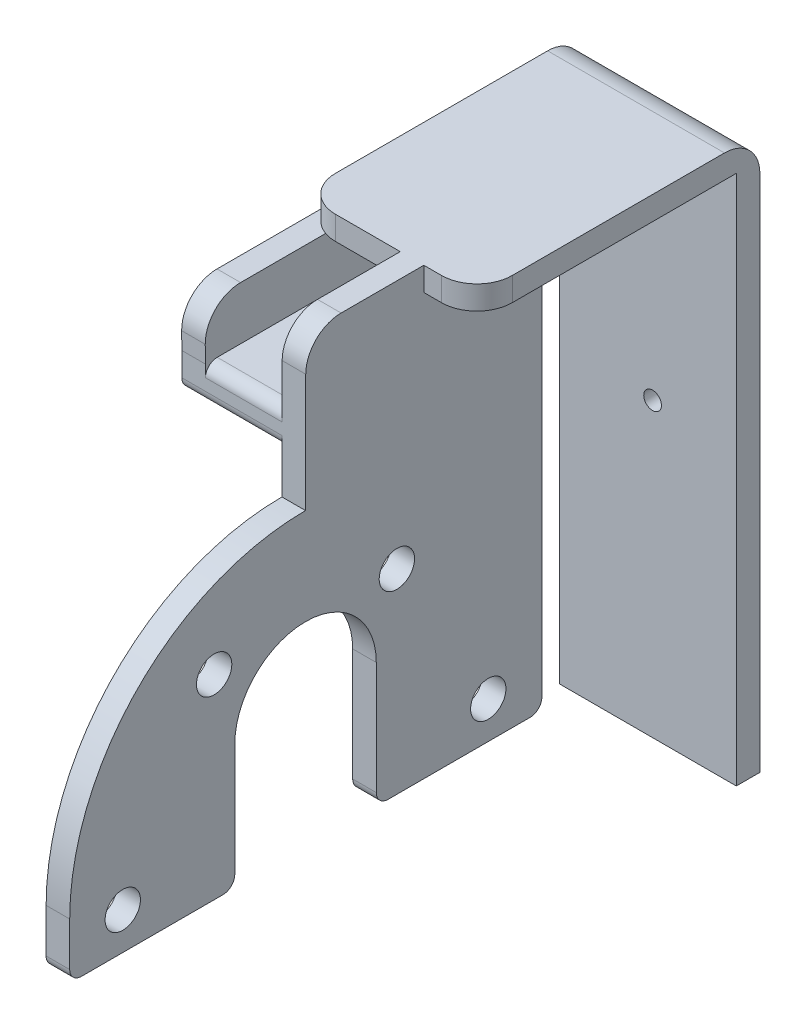
SolidWorks part; units mm, degrees
ref_plane "Front Plane" through (0, 0, 0) normal (0, 0, 1) x (1, 0, 0)
ref_plane "Top Plane" through (0, 0, 0) normal (0, 1, 0) x (1, 0, 0)
ref_plane "Right Plane" through (0, 0, 0) normal (1, 0, 0) x (0, 0, -1)
sketch "Sketch1" plane through (0, 0, 0) normal (0, 1, 0) x (1, 0, 0)
  line L0 (0, 21) -> (0, -134) construction
  line L2 (55, -27) -> (55, 27)
  line L3 (55, 27) -> (-55, 27)
  line L4 (-55, -27) -> (-55, 27)
  line L5 (55, -27) -> (-55, 27) construction
  line L6 (55, 27) -> (-55, -27) construction
  line L7 (-38.5, -134) -> (38.5, -134)
  line L8 (-55, -27) -> (-38.5, -134)
  line L9 (55, -27) -> (38.5, -134)
  line L10 (0, -134) -> (0, -281.2906)
  line L11 (64, -159) -> (-64, -159)
  line L12 (64, -159) -> (64, -134)
  line L13 (64, -134) -> (-64, -134)
  line L14 (-64, -159) -> (-64, -134)
  line L15 (64, -159) -> (-64, -134) construction
  line L16 (64, -134) -> (-64, -159) construction
  line L17 (31, -159) -> (-31, -159)
  line L18 (31, -159) -> (31, -172)
  line L19 (31, -172) -> (-31, -172)
  line L20 (-31, -159) -> (-31, -172)
  line L21 (31, -159) -> (-31, -172) construction
  line L22 (31, -172) -> (-31, -159) construction
  line L23 (64, -172) -> (-64, -172)
  line L24 (64, -172) -> (64, -203)
  line L25 (64, -203) -> (-64, -203)
  line L26 (-64, -172) -> (-64, -203)
  line L27 (64, -172) -> (-64, -203) construction
  line L28 (64, -203) -> (-64, -172) construction
  line L29 (0, 21) -> (0, 27)
  point P0 (0, 0)
  point P10 (0, -134)
  point P11 (0, -146.5)
  point P16 (0, -165.5)
  point P21 (0, -187.5)
  point P26 (0, -134)
  point P28 (0, -159)
  point P29 (0, 27)
  point P33 (0, -172)
  dimension "D1" = 110
  dimension "D2" = 54
  dimension "D3" = 155
  dimension "D4" = 77
  dimension "D5" = 25
  dimension "D6" = 31
  dimension "D7" = 13
  dimension "D8" = 128
  dimension "D9" = 128
  dimension "D10" = 62
  dimension "D11" = 230
  dimension "D12" = 107
extrude "Boss-Extrude1" add sketch "Sketch1" along normal blind 2
sketch "Sketch2" plane through (-55, 0, 0) normal (-1, 0, 0) x (0, 0, 1)
  line L0 (-27, 2) -> (-23, 2)
  line L1 (27, 2) -> (-27, 2) construction
  line L2 (-23, 2) -> (17, 2)
  line L3 (-23, 2) -> (-23, 42)
  line L4 (17, 2) -> (17, 42)
  line L5 (-23, 24) -> (17, 24) construction
  arc A0 (-23, 24) -> (17, 24) centre (-3, 24) cw
  point P5 (-23, 24)
  point P11 (-3, 24)
  line M8 (27, 2) -> (-27, 2)
  dimension "D1" = 4
  dimension "D2" = 40
  dimension "D3" = 40
  dimension "D4" = 40
  dimension "D5" = 22
extrude "Boss-Extrude2" add sketch "Sketch2" against normal blind 2 contours A0 L5 | L5 L3 L4 M8
sketch "Sketch3" plane through (-55, 0, 0) normal (-1, 0, 0) x (0, 0, 1)
  line L0 (-3, 0) -> (-3, 16)
  line L1 (27, 0) -> (-27, 0) construction
  line L2 (-23, 2) -> (-23, 24) construction
  circle A0 centre (-3, 16) radius 6
  dimension "D3" = 12
  dimension "D1" = 16
  dimension "D2" = 20
extrude "Cut-Extrude1" cut sketch "Sketch3" against normal blind 2
mirror "Mirror1" about plane through (0, 0, 0) normal (1, 0, 0) of "Boss-Extrude2"
mirror "Mirror2" about plane through (0, 0, 0) normal (1, 0, 0) of "Cut-Extrude1"
sketch "Sketch4" plane through (0, 2, 0) normal (0, 1, 0) x (1, 0, 0)
  line L0 (0, 27) -> (0, -33) construction
  line L1 (55, 27) -> (-55, 27) construction
  line L2 (0, -33) -> (0, -103) construction
  line L3 (32, -33) -> (-32, -33) construction
  line L4 (32, -103) -> (-32, -103) construction
  circle A0 centre (-32, -33) radius 1.5
  circle A1 centre (-32, -103) radius 1.5
  circle A2 centre (32, -103) radius 1.5
  circle A3 centre (32, -33) radius 1.5
  point P9 (0, -33)
  point P12 (0, -103)
  dimension "D5" = 3
  dimension "D6" = 3
  dimension "D7" = 3
  dimension "D8" = 3
  dimension "D1" = 60
  dimension "D2" = 70
  dimension "D3" = 64
  dimension "D4" = 64
extrude "Cut-Extrude2" cut sketch "Sketch4" against normal blind 3
sketch "Sketch5" plane through (0, 2, 0) normal (0, 1, 0) x (1, 0, 0)
  line L0 (0, -206.875) -> (0, 38.2082) construction
  line L1 (64, -203) -> (-64, -203) construction
  line L2 (0, -203) -> (0, -196)
  line L3 (42, -196) -> (-42, -196)
  circle A0 centre (0, -196) radius 1.5
  circle A1 centre (-42, -196) radius 1.5
  circle A2 centre (42, -196) radius 1.5
  point P3 (0, -203)
  point P12 (0, -196)
  dimension "D2" = 3
  dimension "D4" = 3
  dimension "D5" = 3
  dimension "D1" = 7
  dimension "D3" = 84
extrude "Cut-Extrude3" cut sketch "Sketch5" against normal blind 3 contours A1 | A0 | A2
sketch "Sketch6" plane through (0, 2, 0) normal (0, 1, 0) x (1, 0, 0)
  line L0 (-48.0712, -203) -> (-48.0712, -189) construction
  line L1 (64, -203) -> (-64, -203) construction
  line L2 (-64, -189) -> (-39, -189) construction
  line L3 (-64, -172) -> (-64, -203) construction
  line L4 (-39, -172) -> (-39, -179)
  line L5 (-31, -172) -> (-64, -172) construction
  line L6 (-49, -189) -> (-64, -189)
  line L7 (-64, -189) -> (-64, -172)
  line L8 (-64, -172) -> (-39, -172)
  line L9 (0, -203) -> (0, -168.3934) construction
  line L10 (64, -189) -> (39, -189) construction
  line L11 (48.0712, -203) -> (48.0712, -189) construction
  line L12 (64, -172) -> (39, -172)
  line L13 (64, -189) -> (64, -172)
  line L14 (49, -189) -> (64, -189)
  line L15 (39, -172) -> (39, -179)
  arc A0 (-39, -179) -> (-49, -189) centre (-49, -179) cw
  arc A1 (39, -179) -> (49, -189) centre (49, -179) ccw
  dimension "D3" = 10
  dimension "D1" = 14
  dimension "D2" = 25
extrude "Cut-Extrude4" cut sketch "Sketch6" against normal blind 3
sketch "Sketch7" plane through (0, 2, 0) normal (0, 1, 0) x (1, 0, 0)
  line L0 (-64, -189) -> (-64, -189.1)
  line L1 (-50.1, -203) -> (-50, -203)
  line L2 (64, -203) -> (-64, -203) construction
  line L3 (-50, -203) -> (-50, -189) construction
  line L4 (-64, -189) -> (-49, -189) construction
  line L5 (-50, -189) -> (-64, -189) construction
  line L6 (-64, -189) -> (-64, -203)
  line L7 (-64, -203) -> (-50, -203)
  line L8 (0, -203) -> (0, -157.4735) construction
  line L9 (50, -189) -> (64, -189) construction
  line L10 (64, -203) -> (50, -203)
  line L11 (64, -189) -> (64, -203)
  line L12 (64, -189) -> (64, -189.1)
  arc A0 (-64, -189.1) -> (-50.1, -203) centre (-50.1, -189.1) ccw
  arc A1 (64, -189.1) -> (50.1, -203) centre (50.1, -189.1) cw
  point P12 (-64, -203)
  line M10 (-64, -189) -> (-64, -203)
  line M11 (-64, -203) -> (64, -203)
  line M12 (64, -203) -> (64, -189)
  dimension "D3" = 13.9
  dimension "D1" = 14
  dimension "D2" = 14
extrude "Cut-Extrude5" cut sketch "Sketch7" against normal blind 3 contours A0 M10 M11 | A1 L10 M12
sketch "Sketch8" plane through (0, 2, 0) normal (0, 1, 0) x (1, 0, 0)
  line L0 (-31, -172) -> (-31.1493, -172)
  line L1 (-39.0492, -179.8505) -> (-39.0501, -180)
  line L2 (-39.0501, -180) -> (-31, -180) construction
  line L3 (-31, -180) -> (-31, -172) construction
  line L4 (-39.0492, -179.8505) -> (-39, -172)
  line L5 (-39, -172) -> (-31, -172)
  line L6 (0, -203) -> (0, -153.8568) construction
  line L7 (50.1, -203) -> (-50.1, -203) construction
  line L8 (31, -180) -> (31, -172) construction
  line L9 (39.0501, -180) -> (31, -180) construction
  line L10 (39, -172) -> (31, -172)
  line L11 (39.0492, -179.8505) -> (39, -172)
  line L12 (39.0492, -179.8505) -> (39.0501, -180)
  line L13 (31, -172) -> (31.1493, -172)
  arc A0 (-49, -189) -> (-39, -179) centre (-49, -179) ccw construction
  arc A1 (-31.1493, -172) -> (-39.0492, -179.8505) centre (-31.1493, -179.9) ccw
  arc A2 (31.1493, -172) -> (39.0492, -179.8505) centre (31.1493, -179.9) cw
  point P11 (-39, -172)
  arc M20 (49, -189) -> (39, -179) centre (49, -179) cw
  line M21 (39, -179) -> (39, -172)
  line M22 (39, -172) -> (31, -172)
  line M44 (-31, -172) -> (-39, -172)
  line M45 (-39, -172) -> (-39, -179)
  arc M46 (-39, -179) -> (-49, -189) centre (-49, -179) cw
  dimension "D2" = 7.9
  dimension "D1" = 8
extrude "Cut-Extrude6" cut sketch "Sketch8" against normal blind 3 contours A1 M44 M45 M46 | A2 M22 M20 M21
sketch "Sketch9" plane through (0, 2, 0) normal (0, 1, 0) x (1, 0, 0)
  line L0 (-38.5, -159) -> (-58.5, -153.641)
  line L1 (-31, -159) -> (-64, -159) construction
  line L2 (-38.5, -134) -> (-38.5, -159) construction
  line L3 (-64, -134) -> (-38.5, -134) construction
  line L4 (-38.5, -134) -> (-58.5, -139.359)
  line L5 (-43.9795, -140.5) -> (-43.9795, -152.5) construction
  line L6 (-63.9795, -146.5) -> (-58.9795, -146.5) construction
  line L7 (-58.9795, -146.5) -> (-43.9795, -146.5) construction
  line L8 (-38.5, -134) -> (-64, -134)
  line L9 (-64, -159) -> (-65.7442, -159)
  line L10 (-65.7442, -159) -> (-65.7442, -134)
  line L11 (-64, -159) -> (-64, -134) construction
  line L12 (-64, -159) -> (-38.5, -159)
  line L13 (0, -213.9591) -> (0, -22.6022) construction
  line L14 (58.9795, -146.5) -> (43.9795, -146.5) construction
  line L15 (63.9795, -146.5) -> (58.9795, -146.5) construction
  line L16 (43.9795, -140.5) -> (43.9795, -152.5) construction
  line L17 (38.5, -134) -> (38.5, -159) construction
  line L18 (64, -159) -> (38.5, -159)
  line L21 (38.5, -134) -> (64, -134)
  line L22 (38.5, -134) -> (58.5, -139.359)
  line L23 (38.5, -159) -> (58.5, -153.641)
  line L24 (-65.7442, -134) -> (-64, -134)
  line L25 (64, -134) -> (65.5507, -134)
  line L26 (65.5507, -134) -> (65.5507, -159)
  line L27 (65.5507, -159) -> (64, -159)
  arc A0 (-58.5, -153.641) -> (-58.5, -139.359) centre (-56.5866, -146.5) cw
  circle A1 centre (-58.9795, -146.5) radius 1.5
  circle A2 centre (-43.9795, -140.5) radius 1.5
  circle A3 centre (-43.9795, -152.5) radius 1.5
  circle A4 centre (43.9795, -152.5) radius 1.5
  circle A5 centre (43.9795, -140.5) radius 1.5
  circle A6 centre (58.9795, -146.5) radius 1.5
  arc A7 (58.5, -153.641) -> (58.5, -139.359) centre (56.5866, -146.5) ccw
  point P17 (-43.9795, -146.5)
  point P42 (43.9795, -146.5)
  dimension "D6" = 3
  dimension "D9" = 3
  dimension "D10" = 3
  dimension "D1" = 75
  dimension "D2" = 75
  dimension "D3" = 20
  dimension "D4" = 20
  dimension "D5" = 5
  dimension "D7" = 15
  dimension "D8" = 12
extrude "Cut-Extrude8" cut sketch "Sketch9" against normal blind 3
sketch "Sketch10" plane through (0, 2, 0) normal (0, 1, 0) x (1, 0, 0)
  line L0 (32, -103) -> (32, -143) construction
  line L1 (-12, -122.9795) -> (-12, -132.9795) construction
  line L2 (-12, -122.9795) -> (-14, -122.9795) construction
  line L3 (-12, -132.9795) -> (-14, -132.9795)
  line L4 (-14, -122.9795) -> (34, -122.9795) construction
  line L5 (-14, -132.9795) -> (34, -132.9795) construction
  line L6 (32, -123) -> (34, -122.9795) construction
  line L7 (34, -122.9795) -> (34, -132.9795) construction
  circle A0 centre (-14, -122.9795) radius 1.5
  circle A1 centre (-14, -132.9795) radius 1.5
  circle A2 centre (34, -122.9795) radius 1.5
  circle A3 centre (34, -132.9795) radius 1.5
  point P0 (-32, -103)
  dimension "D5" = 3
  dimension "D6" = 3
  dimension "D9" = 3
  dimension "D10" = 3
  dimension "D2" = 10
  dimension "D3" = 2
  dimension "D4" = 2
  dimension "D7" = 48
  dimension "D8" = 48
  dimension "D11" = 2
extrude "Cut-Extrude9" cut sketch "Sketch10" against normal blind 3
sketch "Sketch12" plane through (55, 0, 0) normal (1, 0, 0) x (0, 0, -1)
  line L0 (-17, 2) -> (23, 2)
  line L1 (3, 2) -> (3, 9)
  line L2 (10.75, 9) -> (-4.75, 9)
  line L3 (-7.9593, 2) -> (-7.9593, 22) construction
  line L4 (3, 2) -> (3, 22.42) construction
  line L5 (18.5, 22.42) -> (-12.5, 22.42) construction
  line L6 (3, 2) -> (3, 35.84) construction
  line L7 (10.75, 35.84) -> (-4.75, 35.84)
  line L8 (-3, 16) -> (-3, 29.84)
  line L9 (9, 16) -> (9, 29.84)
  circle A0 centre (-4.75, 9) radius 1.5
  circle A1 centre (10.75, 9) radius 1.5
  circle A2 centre (-12.5, 22.42) radius 1.5
  circle A3 centre (18.5, 22.42) radius 1.5
  circle A4 centre (-4.75, 35.84) radius 1.5
  circle A5 centre (10.75, 35.84) radius 1.5
  arc A7 (9, 29.84) -> (-3, 29.84) centre (3, 29.84) ccw
  circle A8 centre (3, 16) radius 6 construction
  arc A9 (-3, 16) -> (9, 16) centre (3, 16) ccw
  point P9 (3, 9)
  point P17 (3, 22.42)
  point P24 (3, 35.84)
  dimension "D3" = 3
  dimension "D4" = 3
  dimension "D8" = 3
  dimension "D9" = 3
  dimension "D12" = 3
  dimension "D13" = 3
  dimension "D14" = 12
  dimension "D15" = 31
  dimension "D17" = 13.42
  dimension "D1" = 15.5
  dimension "D2" = 7
  dimension "D5" = 20
  dimension "D6" = 13.42
  dimension "D7" = 31
  dimension "D10" = 13.42
  dimension "D11" = 15.5
  dimension "D16" = 13.42
  dimension "D18" = 13.42
extrude "Cut-Extrude10" cut sketch "Sketch12" against normal through all both and the other way through all
sketch "Sketch13" plane through (55, 0, 0) normal (1, 0, 0) x (0, 0, -1)
  line L0 (-17, 2) -> (23, 2)
  line L1 (-17, 2) -> (-17, 24) construction
  line L2 (23, 2) -> (23, 24) construction
  line L3 (23, 2) -> (23, 24) construction
  line L4 (-17, 24) -> (-17, 2)
  line L5 (-17, 24) -> (-17, 57)
  line L6 (-17, 57) -> (23.0468, 57)
  line L7 (23.0468, 57) -> (23.0468, 2)
  line L8 (23.0468, 2) -> (23, 2)
  line L9 (23, 2) -> (27, 2) construction
  line L10 (3, 44) -> (-17, 44)
  line L11 (3, 44) -> (3.0234, 57)
  line L12 (-17, 19.2835) -> (-3, 19.2835)
  line L13 (-3, 29.84) -> (-3, 16) construction
  line L14 (9, 19.2835) -> (23.0468, 19.2835)
  line L15 (9, 29.84) -> (9, 16) construction
  arc A0 (23, 24) -> (-17, 24) centre (3, 24) ccw construction
  circle A1 centre (-4.75, 35.84) radius 1.5
  circle A2 centre (-12.5, 22.42) radius 1.5
  circle A3 centre (10.75, 35.84) radius 1.5
  circle A4 centre (18.5, 22.42) radius 1.5
  circle A5 centre (-4.75, 9) radius 1.5
  circle A6 centre (10.75, 9) radius 1.5
  point P11 (-4.75, 9)
  point P12 (10.75, 9)
  point P13 (18.5, 22.42)
  point P16 (10.75, 35.84)
  point P18 (-4.75, 35.84)
  point P20 (-12.5, 22.42)
  point P22 (23.0234, 2)
  point P24 (23, 2)
  circle M5 centre (-4.75, 35.84) radius 1.5
  circle M6 centre (10.75, 35.84) radius 1.5
  circle M7 centre (18.5, 22.42) radius 1.5
  circle M10 centre (-12.5, 22.42) radius 1.5
  arc M11 (-3, 29.84) -> (9, 29.84) centre (3, 29.84) cw
  line M12 (9, 29.84) -> (9, 16)
  line M14 (-3, 16) -> (-3, 29.84)
  line M18 (23, 2) -> (23, 24)
  arc M19 (23, 24) -> (-17, 24) centre (3, 24) ccw
  line M20 (-17, 24) -> (-17, 2)
  dimension "D3" = 3
  dimension "D4" = 3
  dimension "D5" = 3
  dimension "D6" = 3
  dimension "D7" = 3
  dimension "D8" = 3
  dimension "D2" = 55
extrude "Boss-Extrude7" add sketch "Sketch13" along normal blind 2 contours L14 L12 M12 M18 M19 M20 M14 M11 M5 M7 M10 M6 | L14 L7 L6 L11 M18 M19
sketch "Sketch14" plane through (55, 0, 0) normal (-1, 0, 0) x (0, 0, 1)
  line L0 (-13.0351, 57) -> (-13.0351, 53) construction
  line L1 (-3.0234, 57) -> (-23.0468, 57) construction
  line L2 (-13.0351, 55) -> (-37.0351, 55)
  line L3 (-37.0351, 55) -> (-37.0351, 57)
  line L4 (-37.0351, 57) -> (-13.0351, 57)
  line L5 (-13.0351, 57) -> (-13.0351, 55)
  dimension "D1" = 24
  dimension "D2" = 24
  dimension "D3" = 2
extrude "Boss-Extrude8" add sketch "Sketch14" along normal blind 15 from offset 6.5 offset against normal yes
sketch "Sketch15" plane through (0, 55, 0) normal (0, -1, 0) x (1, 0, 0)
  line L0 (46.5, -37.0351) -> (46.5, -35.0351)
  line L1 (46.5, -37.0351) -> (46.5, -13.0351) construction
  line L2 (46.5, -35.0351) -> (61.5, -35.0351)
  line L3 (61.5, -37.0351) -> (61.5, -13.0351) construction
  line L4 (61.5, -35.0351) -> (61.5, -37.0351)
  line L5 (61.5, -37.0351) -> (46.5, -37.0351)
  dimension "D1" = 2
extrude "Boss-Extrude9" add sketch "Sketch15" along normal blind 45
sketch "Sketch16" plane through (55, 0, 0) normal (-1, 0, 0) x (0, 0, 1)
  line L0 (-35.9202, 46.4692) -> (-36.7176, -14.586)
  line L1 (-36.7176, -14.586) -> (219.6312, -17.9339)
  line L2 (219.6312, -17.9339) -> (219.6312, 46.4692)
  line L3 (219.6312, 46.4692) -> (-35.9202, 46.4692)
extrude "Cut-Extrude11" cut sketch "Sketch16" along normal through all
sketch "Sketch17" plane through (55, 0, 0) normal (-1, 0, 0) x (0, 0, 1)
  line L1 (28.915, 88.1474) -> (214.4847, 88.1474)
  line L2 (28.915, 88.1474) -> (28.915, -8.0953)
  line L3 (28.915, -8.0953) -> (214.4847, -8.0953)
  line L4 (214.4847, 88.1474) -> (214.4847, -8.0953)
  line L5 (28.915, 88.1474) -> (214.4847, -8.0953) construction
  line L6 (28.915, -8.0953) -> (214.4847, 88.1474) construction
  point P0 (121.6998, 40.0261)
extrude "Cut-Extrude13" cut sketch "Sketch17" against normal through all
sketch "Sketch18" plane through (0, 0, -37.0351) normal (0, 0, -1) x (-1, 0, 0)
  line L0 (-54, 57) -> (-54, 34.78) construction
  line L1 (-46.5, 57) -> (-61.5, 57) construction
  line L2 (-61.5, 33.5725) -> (-54.4, 33.5725) construction
  line L3 (-61.5, 57) -> (-61.5, 10) construction
  line L4 (-54.4, 33.5725) -> (-54.4, 34.78) construction
  line L5 (-54.4, 34.78) -> (-54, 34.78) construction
  circle A0 centre (-54.4, 34.78) radius 1.5
  point P10 (-54.4, 34.78)
  dimension "D3" = 3
  dimension "D1" = 22.22
  dimension "D2" = 7.1
extrude "Cut-Extrude14" cut sketch "Sketch18" against normal blind 10
sketch "Sketch19" plane through (55, 0, 0) normal (-1, 0, 0) x (0, 0, 1)
  line L1 (-3, 44) -> (-3.0234, 57) construction
  line L6 (-3.0117, 50.5) -> (-3.0063, 47.5)
  line L7 (-3.0117, 50.5) -> (-19.0468, 50.5)
  line L8 (-23.0468, 55) -> (-23.0468, 19.2835) construction
  line L9 (-23.0468, 46.5) -> (-23.0468, 41.9623)
  line L10 (-22.0468, 40.9623) -> (-21.0468, 40.9623)
  line L11 (-20.0468, 41.9623) -> (-20.0468, 43.5)
  line L12 (-16.0468, 47.5) -> (-3.0063, 47.5)
  arc A0 (-20.0468, 43.5) -> (-16.0468, 47.5) centre (-16.0468, 43.5) cw
  arc A1 (-19.0468, 50.5) -> (-23.0468, 46.5) centre (-19.0468, 46.5) ccw
  arc A2 (-23.0468, 41.9623) -> (-22.0468, 40.9623) centre (-22.0468, 41.9623) ccw
  arc A3 (-21.0468, 40.9623) -> (-20.0468, 41.9623) centre (-21.0468, 41.9623) ccw
  point P15 (-23.0468, 50.5)
  point P18 (-23.0468, 40.9623)
  dimension "D1" = 3
  dimension "D4" = 4
  dimension "D5" = 1
  dimension "D2" = 3.5
  dimension "D3" = 3
extrude "Boss-Extrude10" add sketch "Sketch19" along normal up to vertex (8.5 mm away)
fillet "Fillet1" radius 3 1 edges at (56, 57, -3.0234)
fillet "Fillet2" radius 3 2 edges at (61.5, 56, -13.0351) (46.5, 56, -13.0351)
fillet "Fillet3" radius 3 1 edges at (54, 57, -37.0351)
sketch "Sketch21" plane through (0, 0, -37.0351) normal (0, 0, -1) x (-1, 0, 0)
  line L0 (-61.5, 54) -> (-46.5, 54)
  line L1 (-46.5, 54) -> (-46.5, 10)
  line L2 (-46.5, 10) -> (-61.5, 10) construction
  line L3 (-46.5, 54) -> (-46.5, 10) construction
  line L4 (-46.5, 10) -> (-61.5, 10)
  line L5 (-61.5, 54) -> (-61.5, 10) construction
  line L6 (-61.5, 10) -> (-61.5, 54)
  circle A0 centre (-54.4, 34.78) radius 0.75
  point P4 (-54.4, 34.78)
  dimension "D1" = 1.5
extrude "Boss-Extrude11" add sketch "Sketch21" against normal blind 2
sketch "Sketch22" plane through (46.5, 0, 0) normal (-1, 0, 0) x (0, 0, 1)
  line L0 (-23.0468, 55) -> (-23.0468, 42.5685)
  line L1 (-35.0351, 55) -> (-16.0351, 55) construction
  line L2 (-23.0468, 55) -> (-13.0351, 55) construction
  line L3 (-23.0468, 55) -> (-2.9586, 55)
  line L4 (-2.9586, 55) -> (-3.0117, 50.5)
  line L5 (-3.0117, 50.5) -> (-3.0063, 47.5)
  line L6 (-23.0468, 46.5) -> (-23.0468, 41.9623) construction
  line L7 (-23.0468, 42.5685) -> (-3.7805, 42.5685)
  line L8 (-3.7805, 42.5685) -> (-3.7805, 47.5)
  line L9 (-16.0468, 47.5) -> (-3.0063, 47.5) construction
  line L10 (-3.7805, 47.5) -> (-3.0063, 47.5)
extrude "Boss-Extrude12" add sketch "Sketch22" against normal blind 2
fillet "Fillet4" radius 3 1 edges at (47.5, 55, -2.9586)
fillet "Fillet5" radius 1 2 edges at (51.75, 50.5, -3.0117) (50.75, 47.5, -3.0063)
fillet "Fillet6" radius 1 4 edges at (56, 19.2835, 17) (56, 19.2835, 3) (56, 19.2835, -23.0468) (56, 19.2835, -9)
